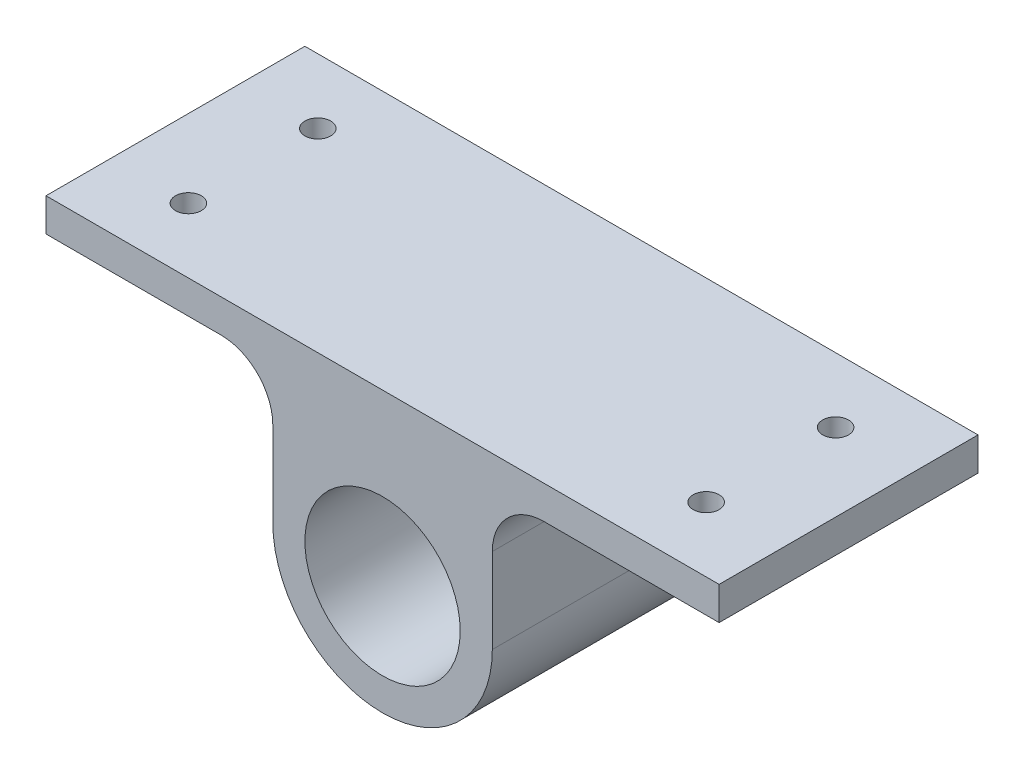
SolidWorks part; units mm, degrees
ref_plane "Front Plane" through (0, 0, 0) normal (0, 0, 1) x (1, 0, 0)
ref_plane "Top Plane" through (0, 0, 0) normal (0, 1, 0) x (1, 0, 0)
ref_plane "Right Plane" through (0, 0, 0) normal (1, 0, 0) x (0, 0, -1)
sketch "Sketch1" plane through (0, 0, 0) normal (0, 0, 1) x (1, 0, 0)
  line L0 (0, 0) -> (0, 193.4646) construction
  line L1 (-106, 0) -> (106, 0) construction
  line L2 (-106, 0) -> (-106, 132)
  line L3 (-106, 132) -> (-325, 132)
  line L4 (-325, 132) -> (-325, 164)
  line L5 (-325, 164) -> (325, 164)
  line L6 (106, 0) -> (106, 132)
  line L7 (106, 132) -> (325, 132)
  line L8 (325, 132) -> (325, 164)
  arc A0 (-106, 0) -> (106, 0) centre (0, 0) ccw
  circle A1 centre (0, 0) radius 75
  point P13 (0, 164)
  dimension "D1" = 150
  dimension "D2" = 212
  dimension "D3" = 132
  dimension "D4" = 325
  dimension "D5" = 32
extrude "Boss-Extrude1" add sketch "Sketch1" along normal mid plane 250
fillet "Fillet1" radius 50 2 edges at (-106, 132, 0) (106, 132, 0)
sketch "Sketch2" plane through (0, 164, 0) normal (0, 1, 0) x (1, 0, 0)
  line L0 (0, -125) -> (0, 125) construction
  line L1 (325, -125) -> (-325, -125) construction
  line L2 (325, 125) -> (-325, 125) construction
  line L3 (-325, -125) -> (-325, 125) construction
  circle A0 centre (-250, 62.5) radius 12.5
  circle A1 centre (-250, -62.5) radius 12.5
  circle A2 centre (250, -62.5) radius 12.5
  circle A3 centre (250, 62.5) radius 12.5
  dimension "D1" = 25
  dimension "D2" = 25
  dimension "D3" = 75
  dimension "D4" = 62.5
  dimension "D5" = 125
  dimension "D6" = 75
  dimension "D7" = 62.5
extrude "Cut-Extrude1" cut sketch "Sketch2" against normal through all
